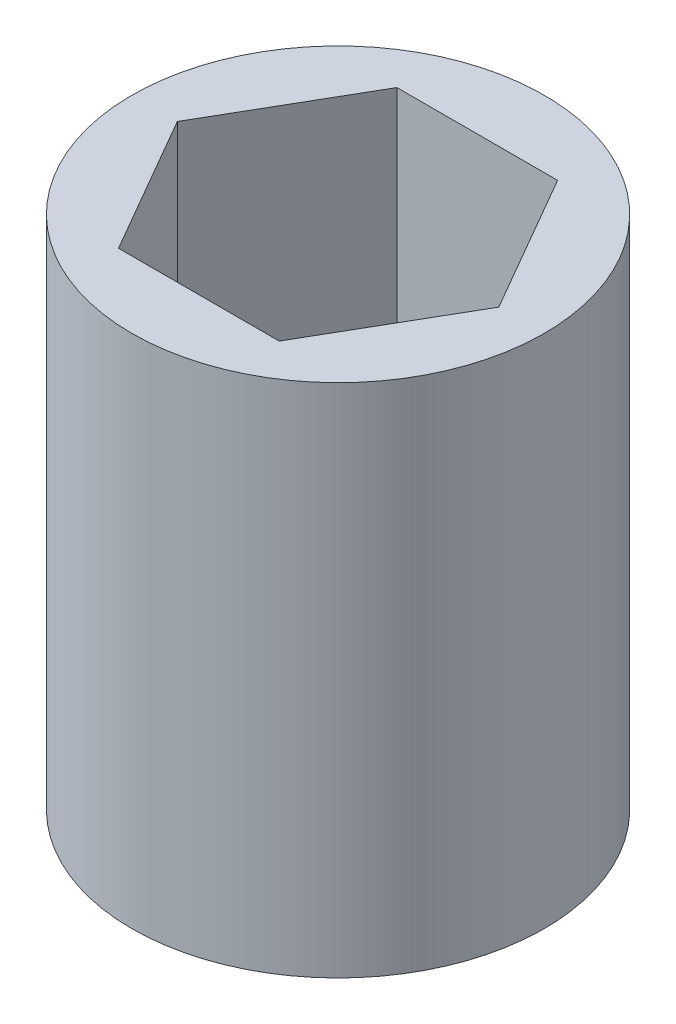
SolidWorks part; units mm, degrees
ref_plane "Front Plane" through (0, 0, 0) normal (0, 0, 1) x (1, 0, 0)
ref_plane "Top Plane" through (0, 0, 0) normal (0, 1, 0) x (1, 0, 0)
ref_plane "Right Plane" through (0, 0, 0) normal (1, 0, 0) x (0, 0, -1)
sketch "Sketch1" plane through (0, 0, 0) normal (0, 1, 0) x (1, 0, 0)
  line L1 (7.9189, 0) -> (3.9595, 6.858)
  line L2 (3.9595, 6.858) -> (-3.9595, 6.858)
  line L3 (-3.9595, 6.858) -> (-7.9189, 0)
  line L4 (-7.9189, 0) -> (-3.9595, -6.858)
  line L5 (-3.9595, -6.858) -> (3.9595, -6.858)
  line L6 (3.9595, -6.858) -> (7.9189, 0)
  circle A0 centre (0, 0) radius 6.858 construction
  circle A1 centre (0, 0) radius 10.16
  dimension "D2" = 20.32
  dimension "D1" = 13.716
extrude "Boss-Extrude1" add sketch "Sketch1" along normal blind 25.4
